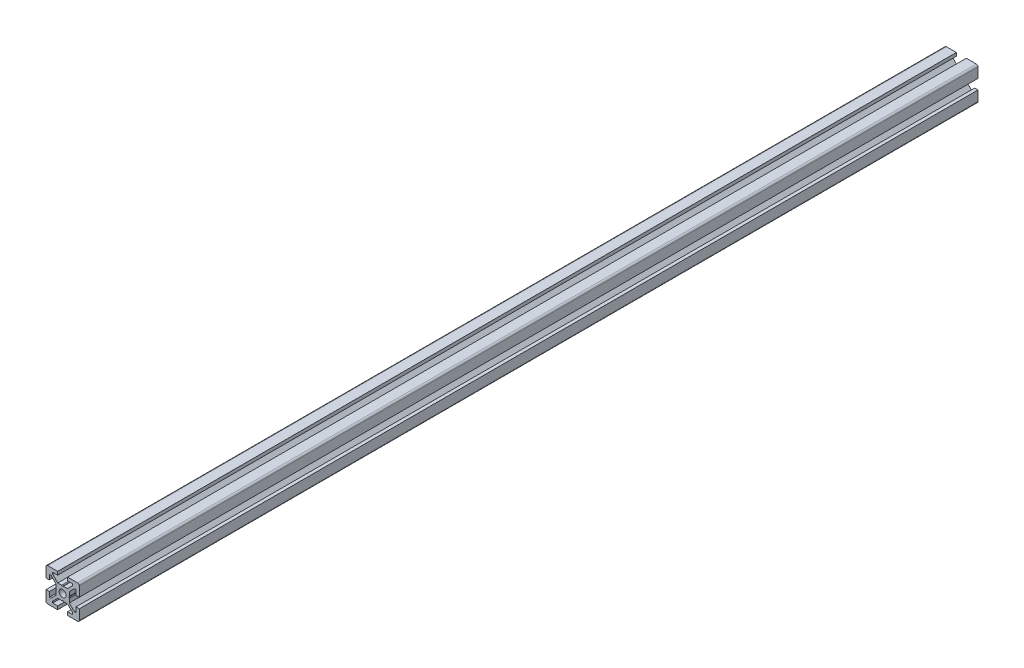
SolidWorks part; units mm, degrees
ref_plane "Front Plane" through (0, 0, 0) normal (0, 0, 1) x (1, 0, 0)
ref_plane "Top Plane" through (0, 0, 0) normal (0, 1, 0) x (1, 0, 0)
ref_plane "Right Plane" through (0, 0, 0) normal (1, 0, 0) x (0, 0, -1)
ref_plane "Plane1" through (0, 0, -500) normal (0, 0, -1) x (-1, 0, 0)
sketch "Sketch1" plane through (0, 0, -500) normal (0, 0, -1) x (-1, 0, 0)
  line L0 (9, 10) -> (3, 10)
  line L1 (3, 10) -> (3, 8)
  line L2 (3, 8) -> (6, 8)
  line L3 (6, 8) -> (6, 7.0607)
  line L4 (6, 7.0607) -> (2.9393, 4)
  line L5 (2.9393, 4) -> (0.5196, 4)
  line L6 (0.5196, 4) -> (0, 3.7)
  line L7 (0, 3.7) -> (-0.5196, 4)
  line L8 (-0.5196, 4) -> (-2.9393, 4)
  line L9 (-2.9393, 4) -> (-6, 7.0607)
  line L10 (-6, 7.0607) -> (-6, 8)
  line L11 (-6, 8) -> (-3, 8)
  line L12 (-3, 8) -> (-3, 10)
  line L13 (-3, 10) -> (-9, 10)
  line L14 (-10, 9) -> (-10, 3)
  line L15 (-10, 3) -> (-8, 3)
  line L16 (-8, 3) -> (-8, 6)
  line L17 (-8, 6) -> (-7.0607, 6)
  line L18 (-7.0607, 6) -> (-4, 2.9393)
  line L19 (-4, 2.9393) -> (-4, 0.5196)
  line L20 (-4, 0.5196) -> (-3.7, 0)
  line L21 (-3.7, 0) -> (-4, -0.5196)
  line L22 (-4, -0.5196) -> (-4, -2.9393)
  line L23 (-4, -2.9393) -> (-7.0607, -6)
  line L24 (-7.0607, -6) -> (-8, -6)
  line L25 (-8, -6) -> (-8, -3)
  line L26 (-8, -3) -> (-10, -3)
  line L27 (-10, -3) -> (-10, -9)
  line L28 (-9, -10) -> (-3, -10)
  line L29 (-3, -10) -> (-3, -8)
  line L30 (-3, -8) -> (-6, -8)
  line L31 (-6, -8) -> (-6, -7.0607)
  line L32 (-6, -7.0607) -> (-2.9393, -4)
  line L33 (-2.9393, -4) -> (-0.5196, -4)
  line L34 (-0.5196, -4) -> (0, -3.7)
  line L35 (0, -3.7) -> (0.5196, -4)
  line L36 (0.5196, -4) -> (2.9393, -4)
  line L37 (2.9393, -4) -> (6, -7.0607)
  line L38 (6, -7.0607) -> (6, -8)
  line L39 (6, -8) -> (3, -8)
  line L40 (3, -8) -> (3, -10)
  line L41 (3, -10) -> (9, -10)
  line L42 (10, -9) -> (10, -3)
  line L43 (10, -3) -> (8, -3)
  line L44 (8, -3) -> (8, -6)
  line L45 (8, -6) -> (7.0607, -6)
  line L46 (7.0607, -6) -> (4, -2.9393)
  line L47 (4, -2.9393) -> (4, -0.5196)
  line L48 (4, -0.5196) -> (3.7, 0)
  line L49 (3.7, 0) -> (4, 0.5196)
  line L50 (4, 0.5196) -> (4, 2.9393)
  line L51 (4, 2.9393) -> (7.0607, 6)
  line L52 (7.0607, 6) -> (8, 6)
  line L53 (8, 6) -> (8, 3)
  line L54 (8, 3) -> (10, 3)
  line L55 (10, 3) -> (10, 9)
  circle A0 centre (0, 0) radius 2.1
  arc A1 (10, 9) -> (9, 10) centre (9, 9) ccw
  arc A2 (-9, 10) -> (-10, 9) centre (-9, 9) ccw
  arc A3 (-10, -9) -> (-9, -10) centre (-9, -9) ccw
  arc A4 (9, -10) -> (10, -9) centre (9, -9) ccw
extrude "Boss-Extrude1" add sketch "Sketch1" against normal blind 540
